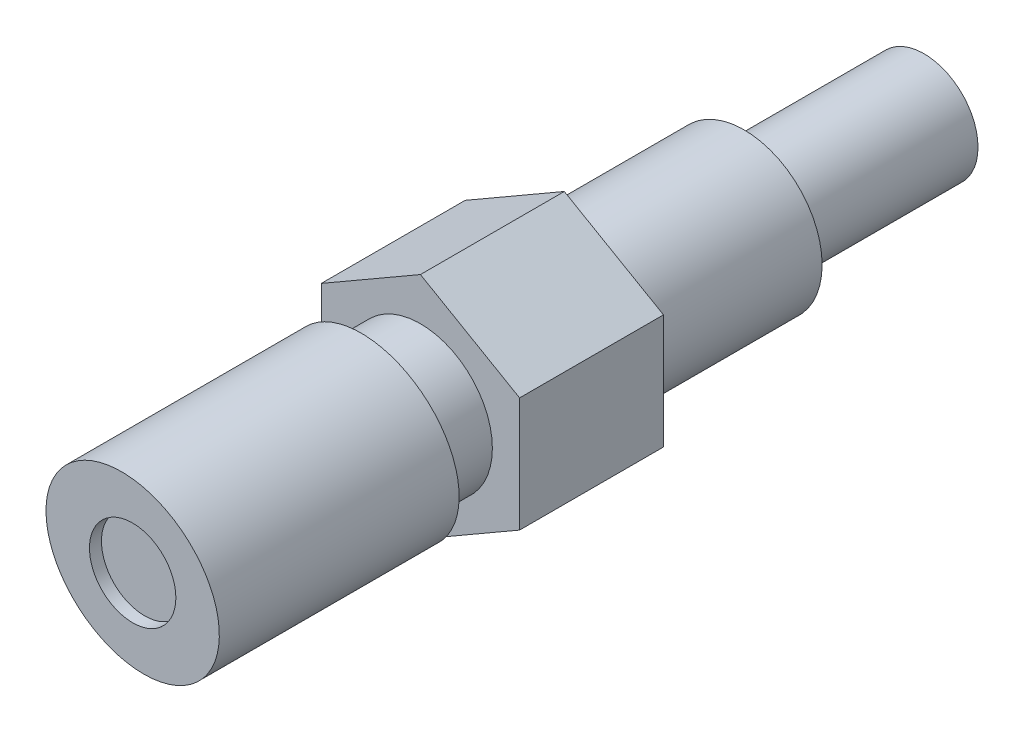
SolidWorks part; units mm, degrees
ref_plane "正面" through (0, 0, 0) normal (0, 0, 1) x (1, 0, 0)
ref_plane "平面" through (0, 0, 0) normal (0, 1, 0) x (1, 0, 0)
ref_plane "右側面" through (0, 0, 0) normal (1, 0, 0) x (0, 0, -1)
sketch "ｽｹｯﾁ1" plane through (0, 0, 0) normal (0, 0, 1) x (1, 0, 0)
  circle A0 centre (0, 0) radius 4.5
  dimension "D1" = 9
extrude "ﾎﾞｽ - 押し出し1" add sketch "ｽｹｯﾁ1" along normal blind 15
sketch "ｽｹｯﾁ2" plane through (0, 0, 15) normal (0, 0, 1) x (1, 0, 0)
  circle A2 centre (0, 0) radius 6.5
  circle A3 centre (0, 0) radius 6.5
  dimension "D1" = 2
extrude "ﾎﾞｽ - 押し出し2" add sketch "ｽｹｯﾁ2" along normal blind 15
sketch "ｽｹｯﾁ3" plane through (0, 0, 30) normal (0, 0, 1) x (1, 0, 0)
  line L1 (0, -9.5487) -> (8.2694, -4.7744)
  line L2 (8.2694, -4.7744) -> (8.2694, 4.7744)
  line L3 (8.2694, 4.7744) -> (0, 9.5487)
  line L4 (0, 9.5487) -> (-8.2694, 4.7744)
  line L5 (-8.2694, 4.7744) -> (-8.2694, -4.7744)
  line L6 (-8.2694, -4.7744) -> (0, -9.5487)
  circle A0 centre (0, 0) radius 8.2694 construction
extrude "ﾎﾞｽ - 押し出し3" add sketch "ｽｹｯﾁ3" along normal blind 12
sketch "ｽｹｯﾁ4" plane through (0, 0, 42) normal (0, 0, 1) x (1, 0, 0)
  circle A0 centre (0, 0) radius 6
  dimension "D1" = 12
extrude "ﾎﾞｽ - 押し出し4" add sketch "ｽｹｯﾁ4" along normal blind 4
sketch "ｽｹｯﾁ5" plane through (0, 0, 46) normal (0, 0, 1) x (1, 0, 0)
  ellipse E0 centre (0, 0) end of major axis (6.2584, -4.1561) minor radius 6.5351
extrude "ﾎﾞｽ - 押し出し5" add sketch "ｽｹｯﾁ5" along normal blind 20
sketch "ｽｹｯﾁ6" plane through (0, 0, 66) normal (0, 0, 1) x (1, 0, 0)
  circle A0 centre (0, 0) radius 3.6032
extrude "ｶｯﾄ - 押し出し1" cut sketch "ｽｹｯﾁ6" against normal blind 1
